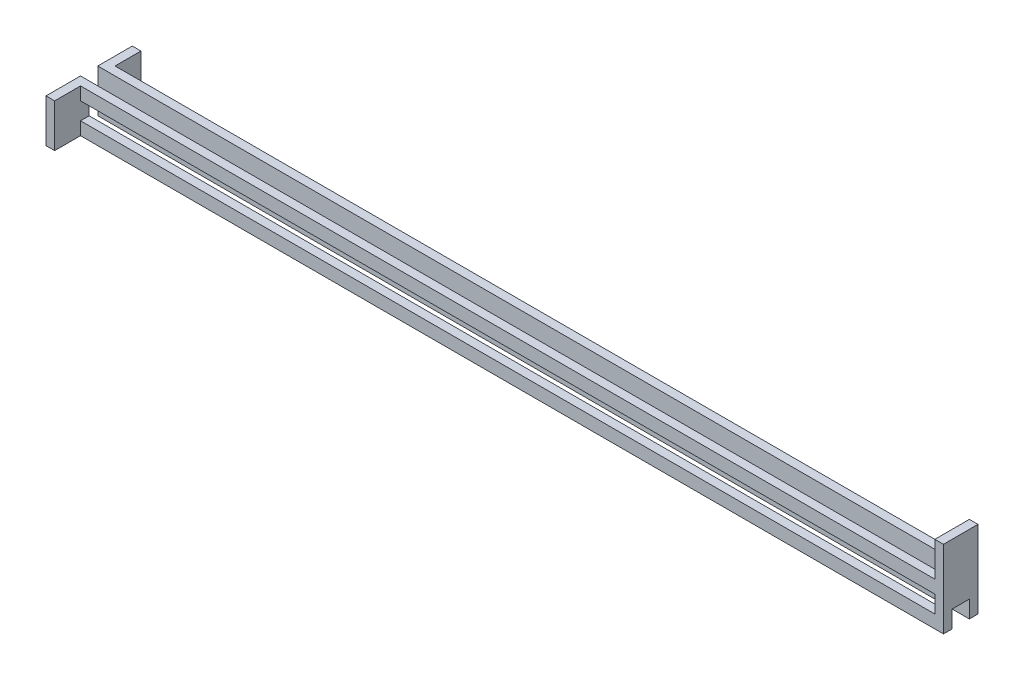
SolidWorks part; units mm, degrees
ref_plane "前视基准面" through (0, 0, 0) normal (0, 0, 1) x (1, 0, 0)
ref_plane "上视基准面" through (0, 0, 0) normal (0, 1, 0) x (1, 0, 0)
ref_plane "右视基准面" through (0, 0, 0) normal (1, 0, 0) x (0, 0, -1)
sketch "草图1" plane through (0, 0, 0) normal (0, 1, 0) x (1, 0, 0)
  line L0 (0, 0) -> (1000, 0)
  line L1 (1000, 0) -> (1000, -20)
  line L2 (1000, -20) -> (0, -20)
  line L3 (0, -20) -> (0, -30.7865)
  line L4 (0, 0) -> (0, 10.7865)
  dimension "D1" = 20
  dimension "D2" = 1000
extrude "拉伸-薄壁1" add sketch "草图1" along normal blind 60 thin thin type one direction wall 10
sketch "草图2" plane through (0, 60, 0) normal (0, 1, 0) x (1, 0, 0)
  line L0 (1010, 10) -> (10, 10) construction
  line L1 (1000, 10) -> (1010, 10)
  line L2 (1000, 10) -> (1000, -30)
  line L3 (1000, -30) -> (1010, -30)
  line L4 (1010, 10) -> (1010, -30)
  line L5 (1000, -20) -> (1000, 0) construction
extrude "凸台-拉伸1" add sketch "草图2" along normal blind 30
ref_plane "基准面1" through (0, 0, 10) normal (0, 0, 1) x (1, 0, 0)
sketch "草图3" plane through (0, 0, 0) normal (-1, 0, 0) x (0, 0, 1)
  line L1 (0, 60) -> (-40, 60)
  line L2 (0, 60) -> (0, 0)
  line L3 (0, 0) -> (-40, 0)
  line L4 (-40, 60) -> (-40, 0)
  line L5 (20, 60) -> (60, 60)
  line L6 (20, 60) -> (20, 0)
  line L7 (20, 0) -> (60, 0)
  line L8 (60, 60) -> (60, 0)
  dimension "D1" = 40
  dimension "D2" = 40
extrude "凸台-拉伸2" add sketch "草图3" against normal blind 10
sketch "草图4" plane through (0, 0, 30) normal (0, 0, 1) x (1, 0, 0)
  line L1 (-28.1333, 50) -> (1000, 50)
  line L2 (-28.1333, 50) -> (-28.1333, 75)
  line L3 (-28.1333, 75) -> (1000, 75)
  line L4 (1000, 50) -> (1000, 75)
  line L5 (1000, 90) -> (1000, 60) construction
  line L8 (-60, 40) -> (0, 40) construction
  dimension "D1" = 10
extrude "切除-拉伸1" cut sketch "草图4" against normal through all both and the other way through all
sketch "草图5" plane through (0, 0, 30) normal (0, 0, 1) x (1, 0, 0)
  line L0 (10, 25) -> (1000, 25)
  line L1 (10, 0) -> (10, 50) construction
  line L4 (10, 35) -> (1000, 35)
  line L5 (10, 35) -> (10, 15)
  line L6 (10, 15) -> (1000, 15)
  line L7 (1000, 35) -> (1000, 15)
  line L8 (10, 35) -> (1000, 15) construction
  line L9 (10, 15) -> (1000, 35) construction
  point P1 (505, 25)
  line M5 (10, 50) -> (10, 0)
  dimension "D1" = 20
extrude "切除-拉伸2" cut sketch "草图5" along normal mid plane 32 contours L7 L4 L0 M5 | L7 L0 L6 M5
sketch "草图7" plane through (1010, 0, 0) normal (1, 0, 0) x (0, 0, -1)
  line L1 (0, 50) -> (0, 0) construction
  line L2 (-20, 0) -> (0, 0)
  line L3 (-20, 0) -> (-20, 20)
  line L4 (-20, 20) -> (0, 20)
  line L5 (0, 0) -> (0, 20)
  dimension "D1" = 20
extrude "切除-拉伸3" cut sketch "草图7" against normal through all both and the other way through all
